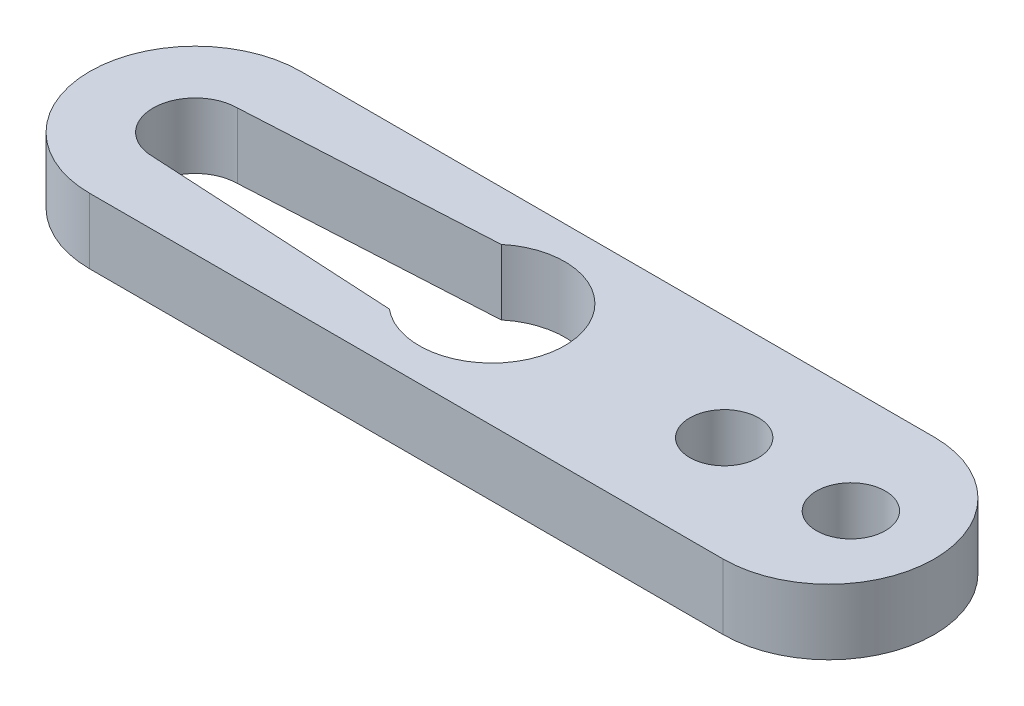
SolidWorks part; units mm, degrees
ref_plane "Front Plane" through (0, 0, 0) normal (0, 0, 1) x (1, 0, 0)
ref_plane "Top Plane" through (0, 0, 0) normal (0, 1, 0) x (1, 0, 0)
ref_plane "Right Plane" through (0, 0, 0) normal (1, 0, 0) x (0, 0, -1)
sketch "Sketch1" plane through (0, 0, 0) normal (0, 1, 0) x (1, 0, 0)
  line L0 (-15, 0) -> (15, 0) construction
  line L1 (-15, 5) -> (15, 5)
  line L2 (-15, -5) -> (15, -5)
  line L3 (-0.95, 0) -> (-3.1591, 2.65) construction
  line L4 (-0.95, 0) -> (-3.1591, -2.65) construction
  line L5 (-3.1591, 2.65) -> (-3.1591, -2.65) construction
  line L6 (-15, 2) -> (-3.1591, 2.65)
  line L7 (-15, -2) -> (-3.1591, -2.65)
  arc A0 (-15, 5) -> (-15, -5) centre (-15, 0) ccw
  arc A1 (15, -5) -> (15, 5) centre (15, 0) ccw
  arc A2 (-15, -2) -> (-15, 2) centre (-15, 0) cw
  arc A3 (-3.1591, -2.65) -> (-3.1591, 2.65) centre (-0.95, 0) ccw
  point P3 (0, 0)
  dimension "D2" = 5
  dimension "D3" = 2
  dimension "D4" = 3.45
  dimension "D5" = 14.05
  dimension "D1" = 30
  dimension "D6" = 100.37
  dimension "D7" = 11.8409
extrude "Boss-Extrude1" add sketch "Sketch1" along normal blind 3 and the other way blind 0.1
hole_wizard "#4 Clearance Hole1" positions "Sketch2" profile "Sketch3" hole size "#4" standard "ANSI Inch" end condition through all
sketch "Sketch2" plane through (0, 3, 0) normal (0, 1, 0) x (1, 0, 0)
  arc A1 (-3.1591, -2.65) -> (-3.1591, 2.65) centre (-0.95, 0) ccw construction
  point P0 (10.05, 0)
  point P2 (16.05, 0)
  point P16 (0, 0)
  dimension "D1" = 11
  dimension "D2" = 6
sketch "Sketch3" plane through (10.05, 3, 0) normal (1, 0, 0) x (0, 0, 1)
  line L0 (0, 0) -> (0, 3.1)
  line L1 (0, 3.1) -> (1.6319, 3.1)
  line L2 (1.6319, 3.1) -> (1.6319, 0)
  line L5 (1.6319, 0) -> (0, 0)
  line L11 (0, -6.35) -> (0, 107.95) construction
  dimension "Thru Hole Dia." = 3.2639
  dimension "Thru Hole Depth" = 3.1
